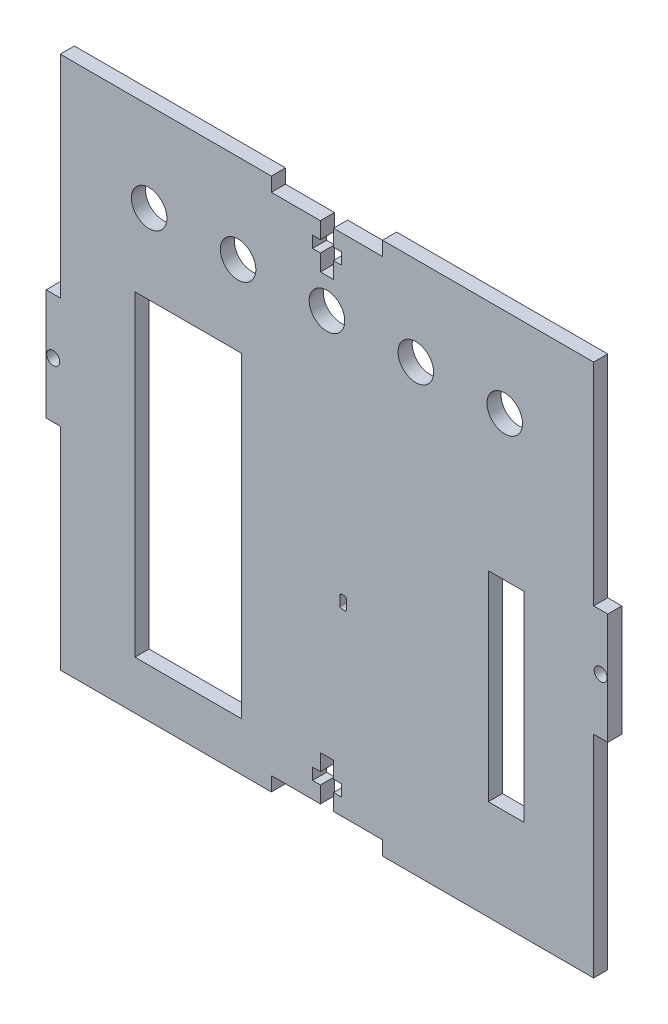
SolidWorks part; units mm, degrees
ref_plane "Front Plane" through (0, 0, 0) normal (0, 0, 1) x (1, 0, 0)
ref_plane "Top Plane" through (0, 0, 0) normal (0, 1, 0) x (1, 0, 0)
ref_plane "Right Plane" through (0, 0, 0) normal (1, 0, 0) x (0, 0, -1)
sketch "Sketch1" plane through (0, 0, 0) normal (0, 0, 1) x (1, 0, 0)
  line L0 (0, 60) -> (0, -60) construction
  line L1 (-60, 60) -> (60, 60)
  line L2 (-60, 60) -> (-60, -60)
  line L3 (-60, -60) -> (60, -60)
  line L4 (60, 60) -> (60, -60)
  line L5 (-60, 60) -> (60, -60) construction
  line L6 (-60, -60) -> (60, 60) construction
  line L7 (-60, 0) -> (60, 0) construction
  line L8 (-3.25, -50.525) -> (3.25, -50.525)
  line L9 (12.5, 60) -> (-12.5, 60)
  line L10 (12.5, 60) -> (12.5, 56.825)
  line L11 (12.5, 56.825) -> (-12.5, 56.825)
  line L12 (-12.5, 60) -> (-12.5, 56.825)
  line L13 (12.5, 60) -> (-12.5, 56.825) construction
  line L14 (12.5, 56.825) -> (-12.5, 60) construction
  line L15 (-1.47, 56.825) -> (1.47, 56.825)
  line L16 (-1.47, 56.825) -> (-1.47, 46.825)
  line L17 (-1.47, 46.825) -> (1.47, 46.825)
  line L18 (1.47, 56.825) -> (1.47, 46.825)
  line L19 (-1.47, 56.825) -> (1.47, 46.825) construction
  line L20 (-1.47, 46.825) -> (1.47, 56.825) construction
  line L21 (-3.25, 53.125) -> (3.25, 53.125)
  line L22 (-3.25, 53.125) -> (-3.25, 50.525)
  line L23 (-3.25, 50.525) -> (3.25, 50.525)
  line L24 (3.25, 53.125) -> (3.25, 50.525)
  line L25 (-3.25, 53.125) -> (3.25, 50.525) construction
  line L26 (-3.25, 50.525) -> (3.25, 53.125) construction
  line L27 (3.25, -53.125) -> (3.25, -50.525)
  line L28 (-3.25, -53.125) -> (3.25, -53.125)
  line L29 (-3.25, -53.125) -> (-3.25, -50.525)
  line L30 (-1.47, -46.825) -> (1.47, -46.825)
  line L31 (1.47, -56.825) -> (1.47, -46.825)
  line L32 (-1.47, -56.825) -> (1.47, -56.825)
  line L33 (-1.47, -56.825) -> (-1.47, -46.825)
  line L34 (12.5, -56.825) -> (-12.5, -56.825)
  line L35 (-12.5, -60) -> (-12.5, -56.825)
  line L36 (12.5, -60) -> (-12.5, -60)
  line L37 (12.5, -60) -> (12.5, -56.825)
  line L38 (63.175, -12.5) -> (60, -12.5)
  line L39 (-63.175, 12.5) -> (-60, 12.5)
  line L40 (-63.175, 12.5) -> (-63.175, -12.5)
  line L41 (-63.175, -12.5) -> (-60, -12.5)
  line L42 (-60, 12.5) -> (-60, -12.5)
  line L43 (-63.175, 12.5) -> (-60, -12.5) construction
  line L44 (-63.175, -12.5) -> (-60, 12.5) construction
  line L45 (60, 12.5) -> (60, -12.5)
  line L46 (63.175, 12.5) -> (60, 12.5)
  line L47 (63.175, 12.5) -> (63.175, -12.5)
  circle A0 centre (-61.5875, 0) radius 1.47
  circle A1 centre (61.5875, 0) radius 1.47
  point P0 (0, 0)
  point P10 (0, 58.4125)
  point P15 (0, 51.825)
  point P20 (0, 51.825)
  point P37 (-61.5875, 0)
  dimension "D11" = 2.94
  dimension "D1" = 120
  dimension "D2" = 120
  dimension "D3" = 3.175
  dimension "D4" = 10
  dimension "D5" = 2.94
  dimension "D6" = 25
  dimension "D7" = 6.5
  dimension "D8" = 2.6
  dimension "D9" = 6.3
  dimension "D10" = 3.175
extrude "Boss-Extrude1" add sketch "Sketch1" along normal mid plane 3.175 contours L21 L24 L23 L18 L17 L16 L22 L11 L12 L1 L2 L3 L4 L10 | L40 L39 L42 L41 | A0 | L38 L45 L46 L47 | A1
sketch "Sketch3" plane through (0, 0, -1.5875) normal (0, 0, -1) x (-1, 0, 0)
  line L0 (-9.6476, 0) -> (-9.6476, -15) construction
  line L5 (-9.6476, -15) -> (-19.2951, -15) construction
  line L6 (-40.3, 7.5) -> (-40.3, -22.5) construction
  line L7 (-36.3, 7.5) -> (-44.3, 7.5)
  line L8 (-36.3, 7.5) -> (-36.3, -37.5)
  line L9 (-36.3, -37.5) -> (-44.3, -37.5)
  line L10 (-44.3, 7.5) -> (-44.3, -37.5)
  line L11 (-38.7125, -40) -> (-38.7125, 10) construction
  line L12 (-41.8875, 10) -> (-41.8875, -40) construction
  line L13 (0, 0) -> (-19.2951, 0) construction
  dimension "D1" = 8
  dimension "D2" = 45
  dimension "D3" = 15
extrude "Cut-Extrude1" cut sketch "Sketch3" against normal through all
sketch "Sketch4" plane through (0, 0, -1.5875) normal (0, 0, -1) x (-1, 0, 0)
  line L0 (43.2, 21.2555) -> (43.2, -48.2445) construction
  line L1 (43.2, 22.1055) -> (19.2, 22.1055)
  line L2 (43.2, 22.1055) -> (43.2, -49.0945)
  line L3 (43.2, -49.0945) -> (19.2, -49.0945)
  line L4 (19.2, 22.1055) -> (19.2, -49.0945)
  line L5 (19.2, -48.2445) -> (19.2, 21.2555) construction
  line L6 (20.05, 22.1055) -> (26.7, 22.1055) construction
  line L7 (42.35, -49.0945) -> (20.05, -49.0945) construction
extrude "Cut-Extrude2" cut sketch "Sketch4" against normal through all
sketch "Sketch5" plane through (0, 0, -1.5875) normal (0, 0, -1) x (-1, 0, 0)
  line L0 (-3.3241, -16.25) -> (-3.9498, -16.25) construction
  line L1 (-3.9498, -13.75) -> (-3.3241, -13.75) construction
  line L2 (-3.1241, -13.95) -> (-3.1241, -16.05) construction
  line L3 (-3.3241, -16.25) -> (-3.9498, -16.25)
  line L4 (-3.9498, -13.75) -> (-3.3241, -13.75)
  line L5 (-3.1241, -13.95) -> (-3.1241, -16.05)
  line L6 (-3.3241, -16.45) -> (-3.9498, -16.45)
  line L7 (-3.9498, -13.55) -> (-3.3241, -13.55)
  line L8 (-2.9241, -13.95) -> (-2.9241, -16.05)
  arc A0 (-3.3241, -16.25) -> (-3.1241, -16.05) centre (-3.3241, -16.05) ccw construction
  arc A1 (-4.1482, -16.0753) -> (-3.9498, -16.25) centre (-3.9498, -16.05) ccw construction
  arc A2 (-4.1482, -13.9247) -> (-4.1482, -16.0753) centre (4.2835, -15) ccw construction
  arc A3 (-3.9498, -13.75) -> (-4.1482, -13.9247) centre (-3.9498, -13.95) ccw construction
  arc A4 (-3.1241, -13.95) -> (-3.3241, -13.75) centre (-3.3241, -13.95) ccw construction
  arc A5 (-3.3241, -16.25) -> (-3.1241, -16.05) centre (-3.3241, -16.05) ccw
  arc A6 (-4.1482, -16.0753) -> (-3.9498, -16.25) centre (-3.9498, -16.05) ccw
  arc A7 (-4.1482, -13.9247) -> (-4.1482, -16.0753) centre (4.2835, -15) ccw
  arc A8 (-3.9498, -13.75) -> (-4.1482, -13.9247) centre (-3.9498, -13.95) ccw
  arc A9 (-3.1241, -13.95) -> (-3.3241, -13.75) centre (-3.3241, -13.95) ccw
  arc A10 (-4.3466, -16.1006) -> (-3.9498, -16.45) centre (-3.9498, -16.05) ccw
  arc A11 (-4.3466, -13.8994) -> (-4.3466, -16.1006) centre (4.2835, -15) ccw
  arc A12 (-3.9498, -13.55) -> (-4.3466, -13.8994) centre (-3.9498, -13.95) ccw
  arc A13 (-2.9241, -13.95) -> (-3.3241, -13.55) centre (-3.3241, -13.95) ccw
  arc A14 (-3.3241, -16.45) -> (-2.9241, -16.05) centre (-3.3241, -16.05) ccw
  dimension "D1" = 0.2
extrude "Cut-Extrude4" cut sketch "Sketch5" against normal through all contours L8 A14 L6 A10 A11 A12 L7 A13
sketch "Sketch6" plane through (0, 0, -1.5875) normal (0, 0, -1) x (-1, 0, 0)
  line L0 (-60, 40) -> (60, 40) construction
  line L1 (-60, 60) -> (-60, 12.5) construction
  line L2 (60, 60) -> (60, 12.5) construction
  line L3 (60, 60) -> (12.5, 60) construction
  line L4 (-40, 40) -> (-20, 40)
  line L5 (-20, 40) -> (0, 40)
  line L6 (0, 40) -> (20, 40)
  line L7 (20, 40) -> (40, 40)
  line L8 (-60, 60) -> (-60, 12.5) construction
  line L9 (0, 40) -> (20, 40)
  line L10 (-20, 40) -> (0, 40)
  line L11 (-40, 40) -> (-20, 40)
  line L12 (-60, 40) -> (-40, 40)
  circle A0 centre (40, 40) radius 4
  circle A1 centre (20, 40) radius 4
  circle A2 centre (0, 40) radius 4
  circle A3 centre (-20, 40) radius 4
  circle A4 centre (-40, 40) radius 4
  dimension "D4" = 8
  dimension "D1" = 20
  dimension "D2" = 20
  dimension "D3" = 20
  dimension "D5" = 5
extrude "Cut-Extrude5" cut sketch "Sketch6" against normal through all contours A0 | A1 | A2 | A3 | A4
